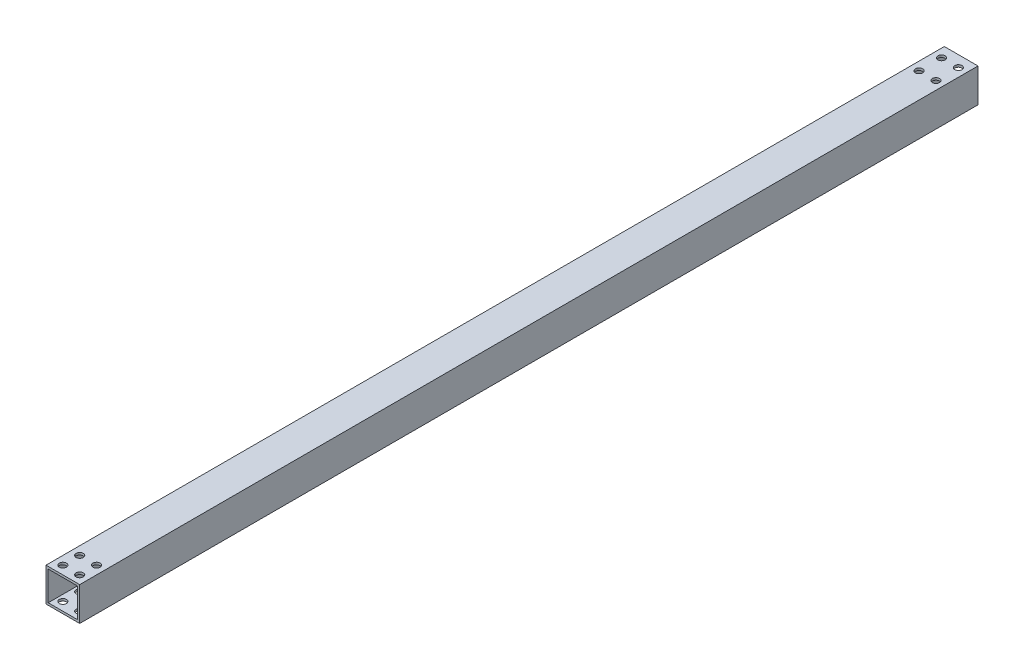
SolidWorks part; units mm, degrees
ref_plane "前视基准面" through (0, 0, 0) normal (0, 0, 1) x (1, 0, 0)
ref_plane "上视基准面" through (0, 0, 0) normal (0, 1, 0) x (1, 0, 0)
ref_plane "右视基准面" through (0, 0, 0) normal (1, 0, 0) x (0, 0, -1)
other "Configuration Table"
sketch "草图1" plane through (0, 0, 0) normal (0, 0, 1) x (1, 0, 0)
  line L1 (0, 0) -> (15, 0)
  line L2 (0, 0) -> (0, -15)
  line L3 (0, -15) -> (15, -15)
  line L4 (15, 0) -> (15, -15)
  dimension "D1" = 15
  dimension "D2" = 15
extrude "拉伸-薄壁1" add sketch "草图1" along normal blind 400 thin
sketch "草图2" plane through (0, 0, 0) normal (0, 1, 0) x (1, 0, 0)
  line L0 (0, -10) -> (15, -10) construction
  line L1 (0, -400) -> (0, 0) construction
  line L2 (15, -400) -> (15, 0) construction
  line L3 (7.5, 0) -> (7.5, -10) construction
  line L4 (15, 0) -> (0, 0) construction
  line L5 (0, -200) -> (15, -200) construction
  line L6 (0, -392.5) -> (15, -392.5) construction
  line L7 (7.5, -392.5) -> (7.5, -400) construction
  line L8 (15, -400) -> (0, -400) construction
  circle A0 centre (3.75, -5) radius 1.6
  circle A1 centre (11.25, -5) radius 1.6
  circle A2 centre (11.25, -15) radius 1.6
  circle A3 centre (3.75, -15) radius 1.6
  circle A8 centre (3.75, -396.25) radius 1.6
  circle A9 centre (11.25, -396.25) radius 1.6
  circle A10 centre (11.25, -388.75) radius 1.6
  circle A11 centre (3.75, -388.75) radius 1.6
  point P30 (5.8336, -399.4961)
  dimension "D2" = 3.2
  dimension "D5" = 3.2
  dimension "D1" = 10
  dimension "D3" = 3.75
  dimension "D4" = 5
  dimension "D6" = 3.75
  dimension "D7" = 3.75
  dimension "D8" = 7.5
extrude "切除-拉伸1" cut sketch "草图2" against normal through all
